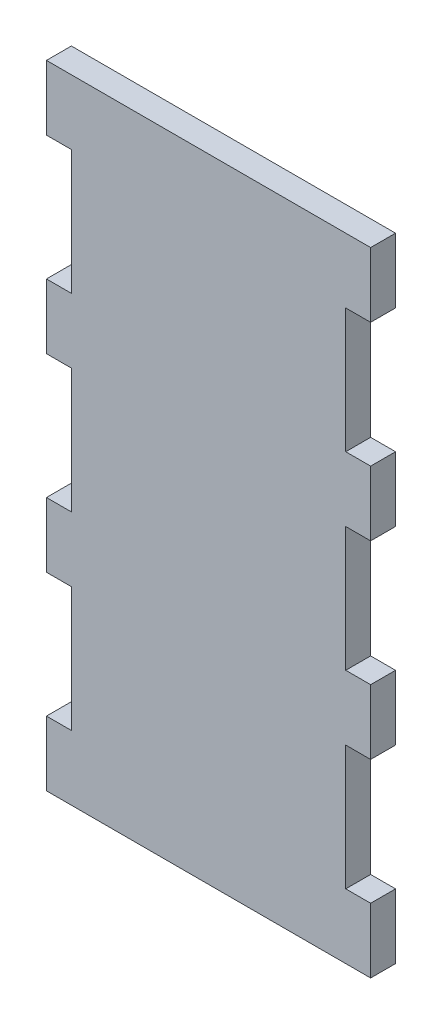
SolidWorks part; units mm, degrees
ref_plane "Front Plane" through (0, 0, 0) normal (0, 0, 1) x (1, 0, 0)
ref_plane "Top Plane" through (0, 0, 0) normal (0, 1, 0) x (1, 0, 0)
ref_plane "Right Plane" through (0, 0, 0) normal (1, 0, 0) x (0, 0, -1)
sketch "Sketch1" plane through (0, 0, 0) normal (0, 0, 1) x (1, 0, 0)
  line L1 (-40.9935, 16.542) -> (-1.9435, 16.542)
  line L2 (-40.9935, 16.542) -> (-40.9935, -59.658)
  line L3 (-40.9935, -59.658) -> (-1.9435, -59.658)
  line L4 (-1.9435, 16.542) -> (-1.9435, -59.658)
  dimension "D1" = 76.2
  dimension "D2" = 39.05
extrude "Boss-Extrude1" add sketch "Sketch1" along normal blind 3
sketch "Sketch2" plane through (0, 0, 3) normal (0, 0, 1) x (1, 0, 0)
  line L0 (-40.9935, 16.542) -> (-40.9935, -59.658) construction
  line L1 (-40.9935, 8.742) -> (-37.9935, 8.742)
  line L2 (-40.9935, 8.742) -> (-40.9935, -6.258)
  line L3 (-40.9935, -6.258) -> (-37.9935, -6.258)
  line L4 (-37.9935, 8.742) -> (-37.9935, -6.258)
  line L5 (-1.9435, 16.542) -> (-40.9935, 16.542) construction
  line L6 (-1.9435, -59.658) -> (-1.9435, 16.542) construction
  line L7 (-1.9435, 8.742) -> (-4.9435, 8.742)
  line L8 (-1.9435, 8.742) -> (-1.9435, -6.258)
  line L9 (-1.9435, -6.258) -> (-4.9435, -6.258)
  line L10 (-4.9435, 8.742) -> (-4.9435, -6.258)
  point P8 (-39.4935, 8.742)
  dimension "D1" = 3
  dimension "D2" = 7.8
  dimension "D3" = 15
  dimension "D4" = 3
  dimension "D5" = 7.8
  dimension "D6" = 15
extrude "Cut-Extrude1" cut sketch "Sketch2" against normal through all
pattern_linear "LPattern1" count 3 spacing 22.8 along (0, -1, 0) of "Cut-Extrude1"
